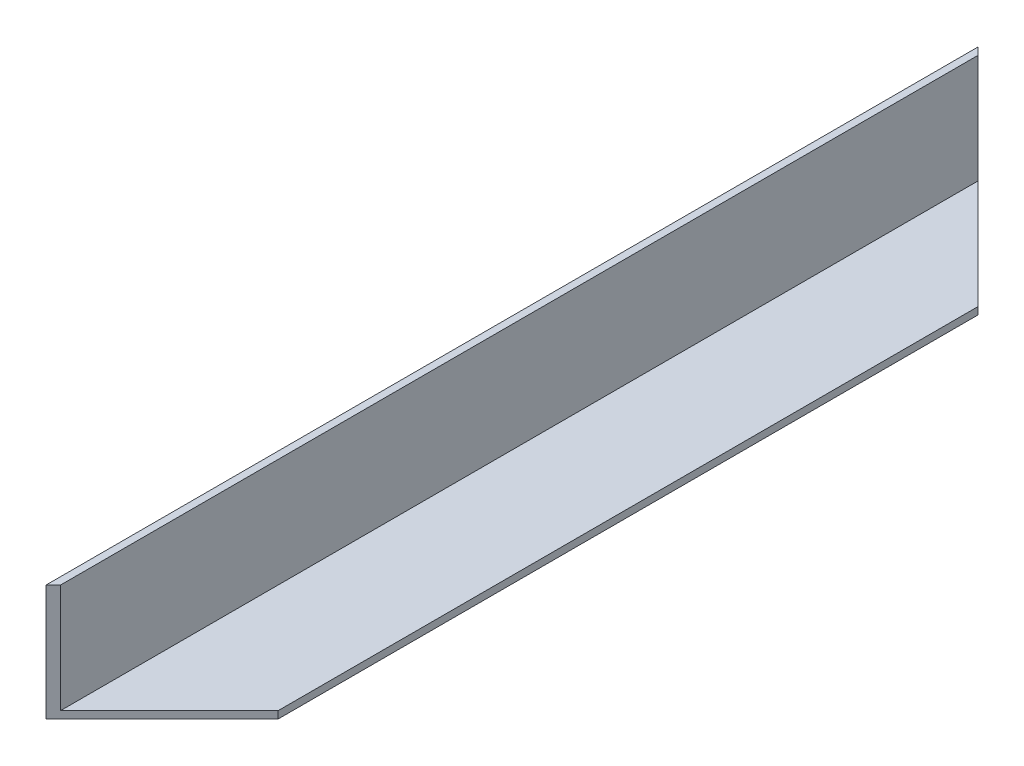
SolidWorks part; units mm, degrees
ref_plane "Front Plane" through (0, 0, 0) normal (0, 0, 1) x (1, 0, 0)
ref_plane "Top Plane" through (0, 0, 0) normal (0, 1, 0) x (1, 0, 0)
ref_plane "Right Plane" through (0, 0, 0) normal (1, 0, 0) x (0, 0, -1)
sketch "Sketch2" plane through (0, 0, 0) normal (0, 0, 1) x (1, 0, 0)
  line L0 (0, 0) -> (0, 30)
  line L1 (0, 0) -> (30, 0)
extrude "Extrude-Thin6" add sketch "Sketch2" along normal blind 257 thin thin type one direction wall 2
sketch "Sketch3" plane through (0, -2, 0) normal (0, 1, 0) x (1, 0, 0)
  line L0 (-2, 0) -> (30, -32)
  line L1 (30, -257) -> (30, 0) construction
  line L2 (-2, 0) -> (30, 0)
  line L3 (30, 0) -> (30, -32)
  line L4 (30, -128.5) -> (122.2642, -128.5) construction
  line L5 (30, -257) -> (30, -225)
  line L6 (-2, -257) -> (30, -225)
  line L7 (-2, -257) -> (30, -257)
  line L8 (-2, -257) -> (-2, 0) construction
  line L9 (-2, 0) -> (0, 0) construction
  dimension "D1" = 32
extrude "Cut-Extrude1" cut sketch "Sketch3" along normal through all
